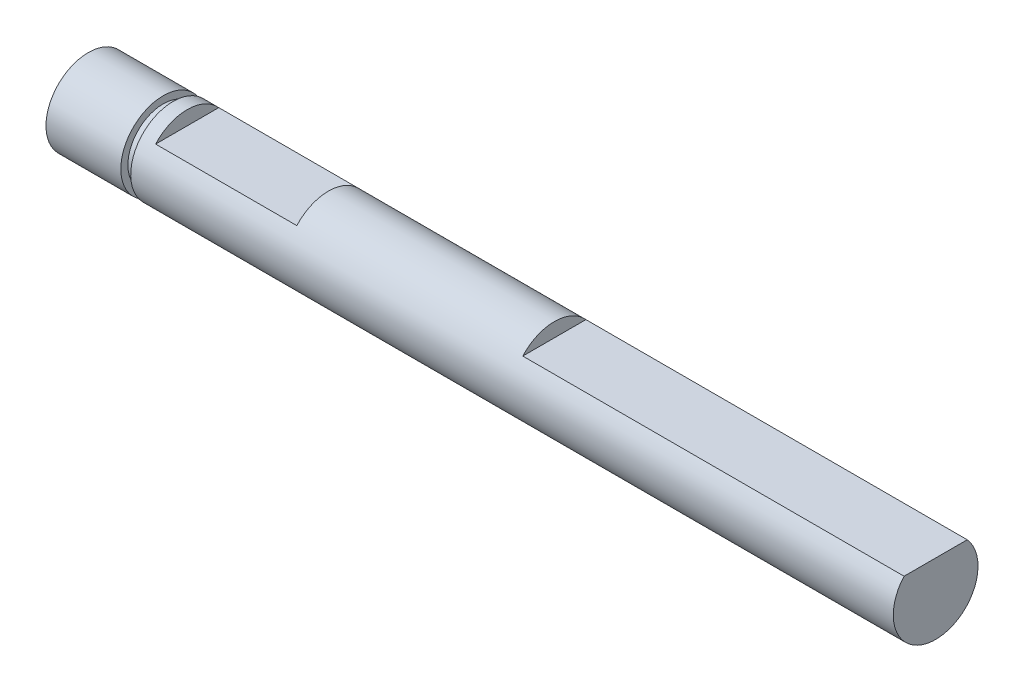
SolidWorks part; units mm, degrees
ref_plane "Plan de face" through (0, 0, 0) normal (0, 0, 1) x (1, 0, 0)
ref_plane "Plan de dessus" through (0, 0, 0) normal (0, 1, 0) x (1, 0, 0)
ref_plane "Plan de droite" through (0, 0, 0) normal (1, 0, 0) x (0, 0, -1)
sketch "Esquisse1" plane through (0, 0, 0) normal (0, 0, 1) x (1, 0, 0)
  line L0 (0, 0) -> (0, 3)
  line L1 (0, 3) -> (5.3, 3)
  line L2 (5.3, 3) -> (5.3, 2.5)
  line L3 (5.3, 2.5) -> (6, 2.5)
  line L4 (6, 2.5) -> (6, 3)
  line L5 (6, 3) -> (60, 3)
  line L6 (60, 3) -> (60, 0)
  line L7 (60, 0) -> (0, 0)
  dimension "D1" = 60
  dimension "D2" = 6
  dimension "D3" = 2.5
  dimension "D4" = 3
  dimension "D5" = 0.7
revolve "Révolution1" add sketch "Esquisse1" angle 360 about L7
ref_plane "Plan1" through (0, 3, 0) normal (0, 1, 0) x (1, 0, 0)
sketch "Esquisse2" plane through (0, 3, 0) normal (0, 1, 0) x (1, 0, 0)
  line L0 (60, -3) -> (60, 3) construction
  line L1 (17, -3) -> (7, -3)
  line L2 (17, -3) -> (17, 3)
  line L3 (17, 3) -> (7, 3)
  line L4 (7, -3) -> (7, 3)
  line L5 (17, -3) -> (7, 3) construction
  line L6 (17, 3) -> (7, -3) construction
  line L7 (33, -3) -> (60, -3)
  line L8 (33, -3) -> (33, 3)
  line L9 (33, 3) -> (60, 3)
  line L10 (60, -3) -> (60, 3)
  line L11 (33, -3) -> (60, 3) construction
  line L12 (33, 3) -> (60, -3) construction
  line L13 (0, 3) -> (0, -3) construction
  point P0 (12, 0)
  point P5 (46.5, 0)
  dimension "D1" = 27
  dimension "D2" = 7
  dimension "D3" = 10
extrude "Enlèv. mat.-Extru.1" cut sketch "Esquisse2" against normal blind 1
